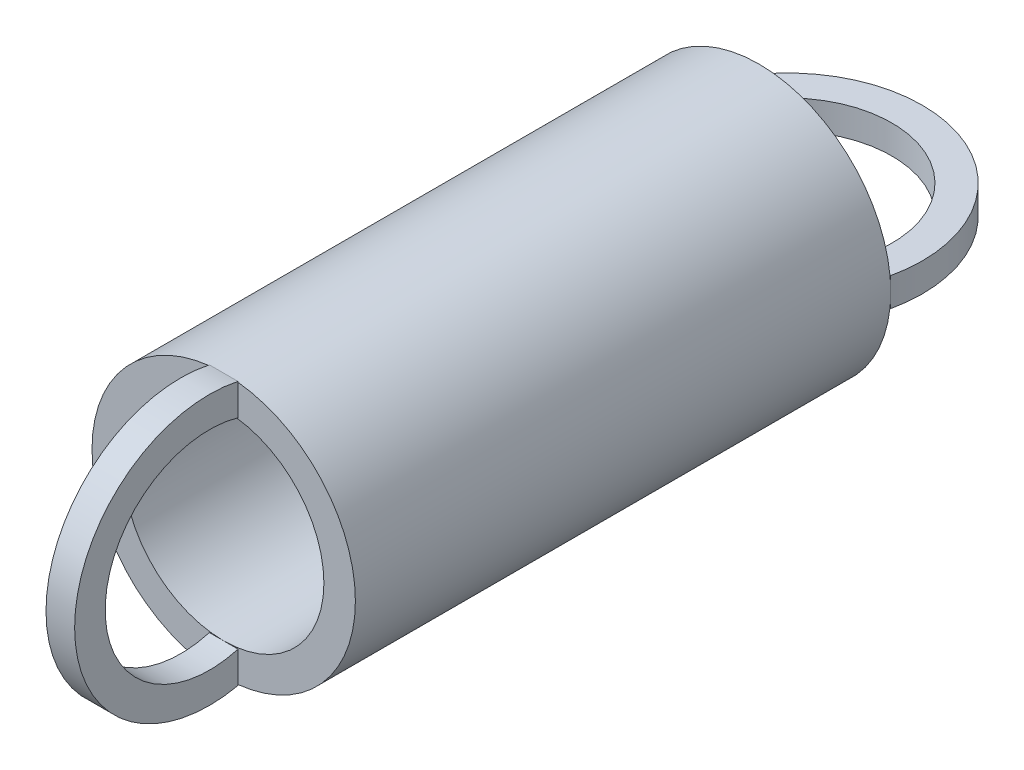
SolidWorks part; units mm, degrees
ref_plane "Front Plane" through (0, 0, 0) normal (0, 0, 1) x (1, 0, 0)
ref_plane "Top Plane" through (0, 0, 0) normal (0, 1, 0) x (1, 0, 0)
ref_plane "Right Plane" through (0, 0, 0) normal (1, 0, 0) x (0, 0, -1)
sketch "Sketch1" plane through (0, 0, 0) normal (0, 0, 1) x (1, 0, 0)
  circle A0 centre (0, 0) radius 4.6
  circle A1 centre (0, 0) radius 3.5
  dimension "D1" = 9.2
  dimension "D2" = 1.1
extrude "Boss-Extrude1" add sketch "Sketch1" along normal mid plane 18.7
sketch "Sketch2" plane through (0, 0, 0) normal (1, 0, 0) x (0, 0, -1)
  line L0 (-9.35, -4.6) -> (-9.35, -3.5)
  line L1 (-9.35, 4.6) -> (-9.35, 3.5)
  line L2 (-9.35, 4.6) -> (-9.35, -4.6) construction
  arc A0 (-9.35, 3.5) -> (-9.35, -3.5) centre (-10.35, 0) ccw
  arc A1 (-9.35, 4.6) -> (-9.35, -4.6) centre (-10.35, 0) ccw
  point P6 (0, 0)
  dimension "D1" = 1
extrude "Boss-Extrude2" add sketch "Sketch2" along normal mid plane 1
sketch "Sketch4" plane through (0, 0, 0) normal (0, 1, 0) x (1, 0, 0)
  line L0 (4.6, 9.35) -> (3.5, 9.35)
  line L1 (-3.5, 9.35) -> (-4.6, 9.35)
  line L2 (4.6, 9.35) -> (-4.6, 9.35) construction
  arc A0 (-3.5, 9.35) -> (3.5, 9.35) centre (0, 10.35) cw
  arc A1 (4.6, 9.35) -> (-4.6, 9.35) centre (0, 10.35) ccw
  dimension "D1" = 1
extrude "Boss-Extrude3" add sketch "Sketch4" along normal mid plane 1
